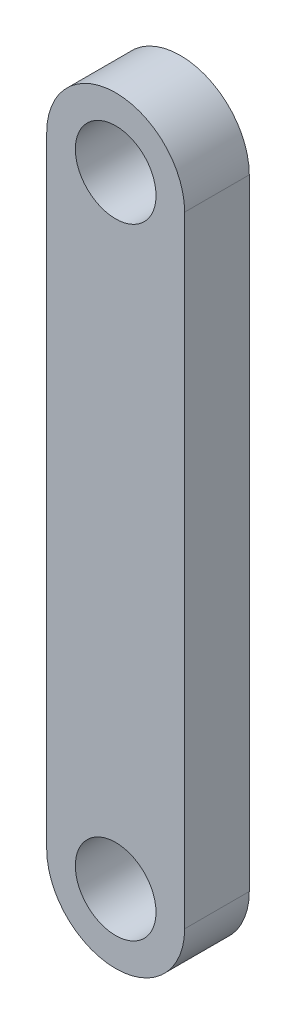
SolidWorks part; units mm, degrees
material "Titanium"
ref_plane "Front Plane" through (0, 0, 0) normal (0, 0, 1) x (1, 0, 0)
ref_plane "Top Plane" through (0, 0, 0) normal (0, 1, 0) x (1, 0, 0)
ref_plane "Right Plane" through (0, 0, 0) normal (1, 0, 0) x (0, 0, -1)
sketch "Sketch1" plane through (0, 0, 0) normal (0, 0, 1) x (1, 0, 0)
  line L3 (-3.2, 28.8) -> (-3.2, 0)
  line L4 (1.65, 0) -> (-1.65, 0) construction
  line L5 (3.2, 28.8) -> (3.2, 0)
  circle A2 centre (0, 0) radius 1.872
  circle A3 centre (0, 28.8) radius 1.872
  arc A4 (3.2, 28.8) -> (-3.2, 28.8) centre (0, 28.8) ccw
  arc A5 (-3.2, 0) -> (3.2, 0) centre (0, 0) ccw
  dimension "D1" = 6.4
  dimension "D2" = 3.744
  dimension "D3" = 28.8
extrude "Boss-Extrude1" add sketch "Sketch1" along normal blind 3
equation "\"bScale\"= 8"
equation "\"lScale\"= 8"
equation "\"D1@Sketch2\"= \"bScale\" * 0.8"
equation "\"D2@Sketch2\"= \"bScale\" * 0.6"
equation "\"D1@Sketch1\"= 0.8 * \"bScale\""
equation "\"D2@Sketch1\"=0.468 * \"bScale\""
equation "\"D3@Sketch1\"=3.6 * \"lScale\""
